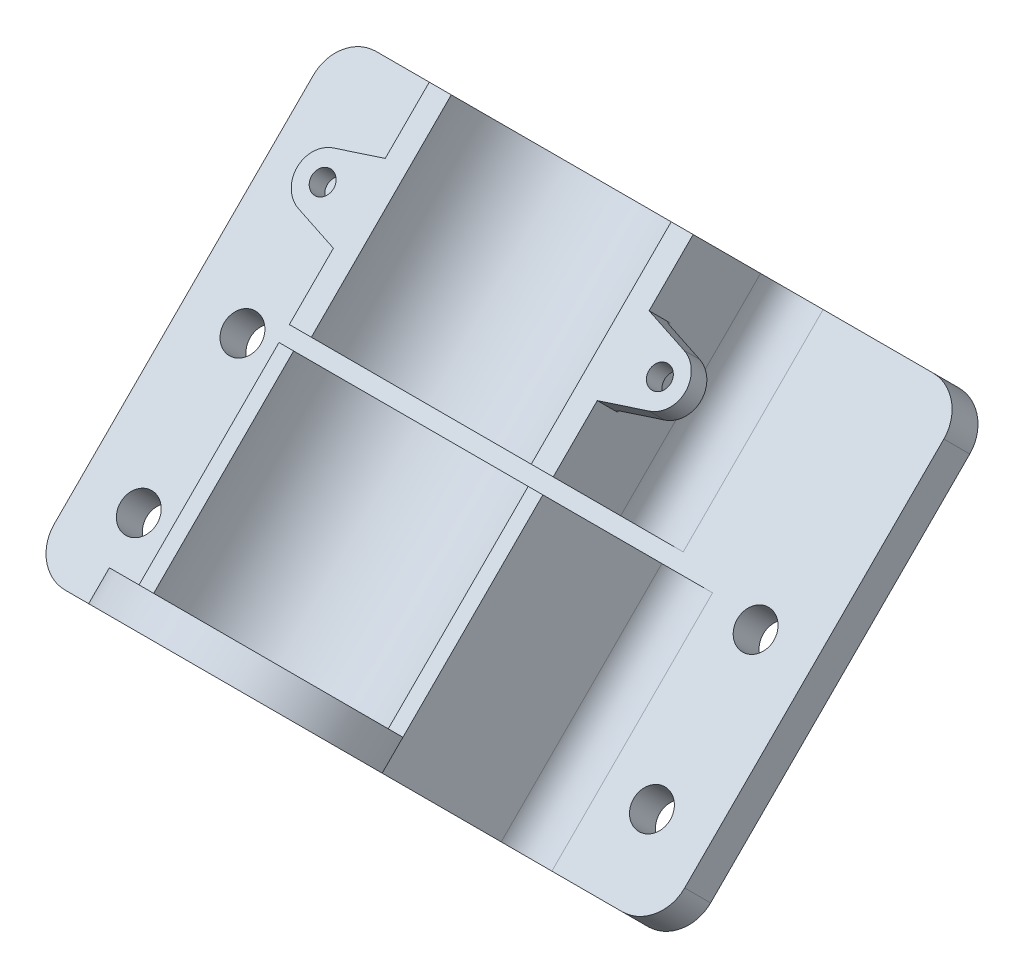
SolidWorks part; units mm, degrees
material "ABS"
ref_plane "Front Plane" through (0, 0, 0) normal (0, 0, 1) x (1, 0, 0)
ref_plane "Top Plane" through (0, 0, 0) normal (0, 1, 0) x (1, 0, 0)
ref_plane "Right Plane" through (0, 0, 0) normal (1, 0, 0) x (0, 0, -1)
sketch "Sketch1" plane through (0, 24.6265, -24.6265) normal (0, -0.7071, 0.7071) x (1, 0, 0)
  line L0 (83.2908, 127.2694) -> (77.1264, 121.1049) construction
  line L1 (64.3984, 133.8329) -> (70.5629, 139.9973) construction
  line L2 (83.2908, 127.2694) -> (77.1264, 121.1049)
  line L3 (64.3984, 133.8329) -> (70.5629, 139.9973)
  circle A0 centre (73.8446, 130.5511) radius 18
  circle A1 centre (73.8446, 130.5511) radius 16
  circle A2 centre (73.8446, 130.5511) radius 16 construction
  arc A3 (64.3984, 133.8329) -> (77.1264, 121.1049) centre (73.8446, 130.5511) ccw construction
  arc A4 (83.2908, 127.2694) -> (70.5629, 139.9973) centre (73.8446, 130.5511) ccw construction
  arc A5 (64.3984, 133.8329) -> (77.1264, 121.1049) centre (73.8446, 130.5511) ccw
  arc A6 (83.2908, 127.2694) -> (70.5629, 139.9973) centre (73.8446, 130.5511) ccw
  dimension "D1" = 0
  dimension "D2" = 2
extrude "Boss-Extrude1" add sketch "Sketch1" along normal up to surface (4 mm away)
sketch "Sketch2" plane through (0, 24.6265, -24.6265) normal (0, 0.7071, -0.7071) x (1, 0, 0)
  circle A0 centre (86.8446, -130.5511) radius 1.5 construction
  circle A1 centre (73.8446, -143.5511) radius 1.5 construction
  circle A2 centre (60.8446, -130.5511) radius 1.5 construction
  circle A3 centre (73.8446, -117.5511) radius 1.5 construction
  circle A4 centre (86.8446, -130.5511) radius 1.5
  circle A5 centre (73.8446, -143.5511) radius 1.5
  circle A6 centre (60.8446, -130.5511) radius 1.5
  circle A7 centre (73.8446, -117.5511) radius 1.5
extrude "Cut-Extrude1" cut sketch "Sketch2" against normal up to next
sketch "Sketch3" plane through (0, 24.6265, -24.6265) normal (0, 0.7071, -0.7071) x (1, 0, 0)
  line L0 (91.8446, -130.5511) -> (89.8446, -130.5511)
  line L1 (57.8446, -130.5511) -> (55.8446, -130.5511)
  arc A0 (89.8446, -130.5511) -> (57.8446, -130.5511) centre (73.8446, -130.5511) ccw
  circle A1 centre (73.8446, -130.5511) radius 18
  arc A2 (91.8446, -130.5511) -> (55.8446, -130.5511) centre (73.8446, -130.5511) ccw
  dimension "D1" = 0
extrude "Boss-Extrude2" add sketch "Sketch3" along normal up to surface (27 mm away)
ref_plane "Plane1" through (0, 79.5857, 79.5857) normal (0, -0.7071, -0.7071) x (-1, 0, 0)
sketch "Sketch4" plane through (0, 79.5857, 79.5857) normal (0, -0.7071, -0.7071) x (-1, 0, 0)
  line L1 (-30.8446, 30.8271) -> (-116.8446, 30.8271)
  line L2 (-30.8446, 30.8271) -> (-30.8446, 90.8271)
  line L3 (-30.8446, 90.8271) -> (-116.8446, 90.8271)
  line L4 (-116.8446, 30.8271) -> (-116.8446, 90.8271)
  line L6 (-73.8446, 61.8271) -> (-73.8446, 30.8271) construction
  line L7 (-55.8446, 61.8271) -> (-91.8446, 61.8271) construction
  point P12 (-73.8446, 30.8271)
  dimension "D1" = 60
  dimension "D2" = 86
extrude "Boss-Extrude5" add sketch "Sketch4" along normal blind 5 separate body
sketch "Sketch6" plane through (0, 21.798, -21.798) normal (0, -0.7071, 0.7071) x (1, 0, 0)
  line L0 (55.8446, 130.5511) -> (48.8446, 112.5511)
  line L1 (116.8446, 112.5511) -> (30.8446, 112.5511) construction
  line L2 (91.8446, 130.5511) -> (98.8446, 112.5511)
  line L3 (98.8446, 112.5511) -> (48.8446, 112.5511)
  line L4 (55.8446, 130.5511) -> (57.8446, 130.5511)
  line L5 (89.8446, 130.5511) -> (91.8446, 130.5511)
  circle A0 centre (73.8446, 130.5511) radius 18 construction
  arc A1 (55.8446, 130.5511) -> (91.8446, 130.5511) centre (73.8446, 130.5511) ccw
  arc A2 (57.8446, 130.5511) -> (89.8446, 130.5511) centre (73.8446, 130.5511) ccw
  circle A3 centre (73.8446, 130.5511) radius 16 construction
  circle A4 centre (73.8446, 130.5511) radius 18 construction
  circle M11 centre (73.8446, 130.5511) radius 18
  dimension "D1" = 25
  dimension "D2" = 25
  dimension "D3" = 2
extrude "Boss-Extrude6" add sketch "Sketch6" against normal up to surface (31 mm away) contours L3 L0 M11 | A2 L4 L5 M11 | L3 L2 M11
sketch "Sketch8" plane through (0, 64.2244, -64.2244) normal (0, 0.7071, -0.7071) x (1, 0, 0)
  line L0 (91.8446, -130.5511) -> (88.8446, -130.5511)
  line L1 (55.8446, -130.5511) -> (55.8446, -112.5511)
  line L2 (30.8446, -112.5511) -> (116.8446, -112.5511) construction
  line L3 (55.8446, -112.5511) -> (91.8446, -112.5511)
  line L4 (91.8446, -112.5511) -> (91.8446, -130.5511)
  line L5 (58.8446, -130.5511) -> (55.8446, -130.5511)
  circle A0 centre (73.8446, -130.5511) radius 15 construction
  arc A1 (88.8446, -130.5511) -> (58.8446, -130.5511) centre (73.8446, -130.5511) ccw
extrude "Boss-Extrude7" add sketch "Sketch8" against normal blind 27 contours L0 A1 L5 L1 L3 L4
sketch "Sketch9" plane through (0, 92.3136, 92.3136) normal (0, 0.7071, 0.7071) x (1, 0, 0)
  line L1 (55.8446, 63.8271) -> (55.8446, 90.8271) construction
  line L2 (91.8446, 63.8271) -> (91.8446, 90.8271) construction
  line L3 (55.8446, 72.3271) -> (49.9192, 73.9516)
  line L4 (49.9192, 80.7025) -> (55.8446, 82.3271)
  line L5 (97.77, 80.7025) -> (91.8446, 82.3271)
  line L6 (97.77, 73.9516) -> (91.8446, 72.3271)
  line L7 (55.8446, 72.3271) -> (55.8446, 82.3271)
  line L8 (91.8446, 72.3271) -> (91.8446, 82.3271)
  circle A0 centre (96.8446, 77.3271) radius 1.5
  circle A1 centre (50.8446, 77.3271) radius 1.5
  arc A2 (49.9192, 80.7025) -> (49.9192, 73.9516) centre (50.8446, 77.3271) ccw
  arc A3 (97.77, 73.9516) -> (97.77, 80.7025) centre (96.8446, 77.3271) ccw
  circle A4 centre (50.8446, 77.3271) radius 3.5 construction
  circle A5 centre (96.8446, 77.3271) radius 3.5 construction
  point P6 (55.8446, 77.3271)
  dimension "D1" = 3
  dimension "D2" = 5
  dimension "D3" = 5
  dimension "D5" = 5
  dimension "D6" = 5
  dimension "D7" = 5
  dimension "D8" = 5
  dimension "D4" = 2
extrude "Boss-Extrude8" add sketch "Sketch9" against normal blind 3
fillet "Fillet2" radius 5 8 edges at (116.8446, 99.6159, 56.0199) (30.8446, 99.6159, 56.0199) (116.8446, 142.0423, 13.5935) (30.8446, 142.0423, 13.5935) (48.8446, 112.3438, 46.8275) (55.8446, 134.2642, 24.9072) (98.8446, 112.3438, 46.8275) (91.8446, 134.2642, 24.9072)
fillet "Fillet3" radius 1 2 edges at (91.8446, 144.8708, 35.5138) (55.8446, 144.8708, 35.5138)
sketch "Sketch10" plane through (0, 79.5857, 79.5857) normal (0, 0.7071, 0.7071) x (1, 0, 0)
  line L0 (111.8446, 30.8271) -> (102.2649, 30.8271) construction
  line L1 (116.8446, 85.8271) -> (116.8446, 35.8271) construction
  line L3 (45.4243, 30.8271) -> (35.8446, 30.8271) construction
  line L4 (30.8446, 35.8271) -> (30.8446, 85.8271) construction
  line L5 (173.8446, 70.8271) -> (-26.1554, 70.8271) construction
  circle A0 centre (108.8446, 40.8271) radius 2.5
  circle A1 centre (38.8446, 40.8271) radius 2.5
  circle A4 centre (108.8446, 60.8271) radius 2.5
  circle A5 centre (38.8446, 60.8271) radius 2.5
  dimension "D1" = 5
  dimension "D6" = 10
  dimension "D2" = 10
  dimension "D3" = 8
  dimension "D4" = 10
  dimension "D5" = 8
  dimension "D7" = 10
extrude "Cut-Extrude2" cut sketch "Sketch10" against normal up to next
